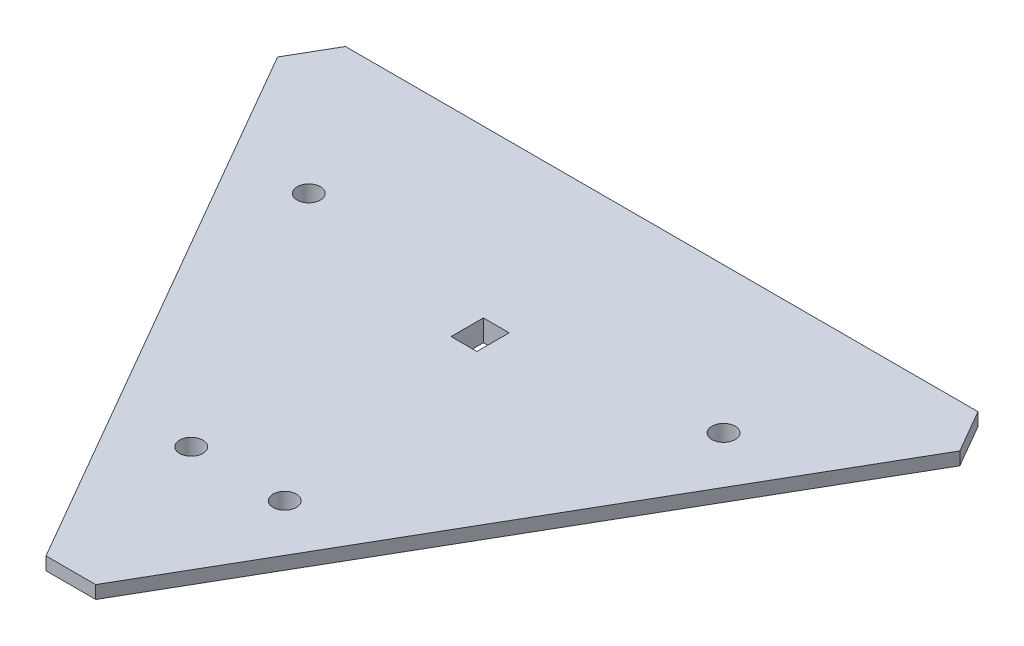
SolidWorks part; units mm, degrees
ref_plane "Front Plane" through (0, 0, 0) normal (0, 0, 1) x (1, 0, 0)
ref_plane "Top Plane" through (0, 0, 0) normal (0, 1, 0) x (1, 0, 0)
ref_plane "Right Plane" through (0, 0, 0) normal (1, 0, 0) x (0, 0, -1)
sketch "Sketch1" plane through (0, 0, 0) normal (0, 1, 0) x (1, 0, 0)
  line L0 (-60, 45.9571) -> (60, 45.9571)
  line L1 (-9.8, -74.9401) -> (-69.8, 28.983)
  line L2 (9.8, -74.9401) -> (69.8, 28.983)
  line L3 (-60, 45.9571) -> (-69.8, 28.983)
  line L4 (-9.8, -74.9401) -> (9.8, -74.9401)
  line L5 (60, 45.9571) -> (69.8, 28.983)
  circle A0 centre (0, 0) radius 45.9571
  dimension "D1" = 60
  dimension "D2" = 60
  dimension "D3" = 60
  dimension "D4" = 120
  dimension "D5" = 120
  dimension "D6" = 120
  dimension "D7" = 19.6
  dimension "D8" = 120
  dimension "D9" = 120
  dimension "D10" = 19.6
extrude "Boss-Extrude1" add sketch "Sketch1" along normal blind 2 contours A0 L0 L3 L1 | A0 | A0 L2 L5 L0 | A0 L1 L4 L2
sketch "Sketch2" plane through (0, 2, 0) normal (0, 1, 0) x (1, 0, 0)
  line L0 (-73.453, 49.0748) -> (-79.2265, 39.0748)
  line L1 (5.7735, -88.1495) -> (79.2265, 39.0748)
  line L2 (73.453, 49.0748) -> (-73.453, 49.0748)
  line L3 (-79.2265, 39.0748) -> (-5.7735, -88.1495)
  line L4 (-5.7735, -88.1495) -> (5.7735, -88.1495)
  line L5 (73.453, 49.0748) -> (79.2265, 39.0748)
  circle A0 centre (0, 0) radius 49.0748 construction
  dimension "D2" = 60
  dimension "D4" = 120
  dimension "D6" = 60
extrude "Boss-Extrude2" add sketch "Sketch2" along normal blind 3 contours L3 L4 L1 L5 L2 L0
sketch "Sketch3" plane through (0, 0, 0) normal (0, 1, 0) x (1, 0, 0)
  line L1 (0, -98.1495) -> (0, 0) construction
  circle A0 centre (-48.1611, 15.268) radius 2.7
  circle A1 centre (-10.8581, -49.3428) radius 2.7
  circle A2 centre (10.8581, -49.3428) radius 2.7
  circle A3 centre (48.1611, 15.268) radius 2.7
  dimension "D1" = 5.4
  dimension "D2" = 5.4
extrude "Cut-Extrude1" cut sketch "Sketch3" along normal through all contours A3 | A0 | A1 | A2
sketch "Sketch5" plane through (0, 0, 0) normal (0, -1, 0) x (1, 0, 0)
  line L1 (8, -2) -> (-8, -2)
  line L2 (8, -2) -> (8, 0)
  line L3 (8, 0) -> (-8, 0)
  line L4 (-8, -2) -> (-8, 0)
  dimension "D1" = 2
  dimension "D2" = 16
  dimension "D3" = 8
  dimension "D4" = 0
extrude "Cut-Extrude2" cut sketch "Sketch5" against normal blind 4
sketch "Sketch6" plane through (0, 0, 0) normal (0, -1, 0) x (1, 0, 0)
  line L0 (8, -2) -> (8, 0) construction
  line L1 (3.15, -10.5) -> (-2.85, -10.5)
  line L2 (3.15, -10.5) -> (3.15, -3)
  line L3 (3.15, -3) -> (-2.85, -3)
  line L4 (-2.85, -10.5) -> (-2.85, -3)
  line L5 (-8, 0) -> (-8, -2) construction
  line L6 (-8, -2) -> (8, -2) construction
  dimension "D1" = 7.5
  dimension "D2" = 6
  dimension "D3" = 4.85
  dimension "D4" = 5.15
  dimension "D5" = 1
extrude "Cut-Extrude3" cut sketch "Sketch6" against normal blind 67
